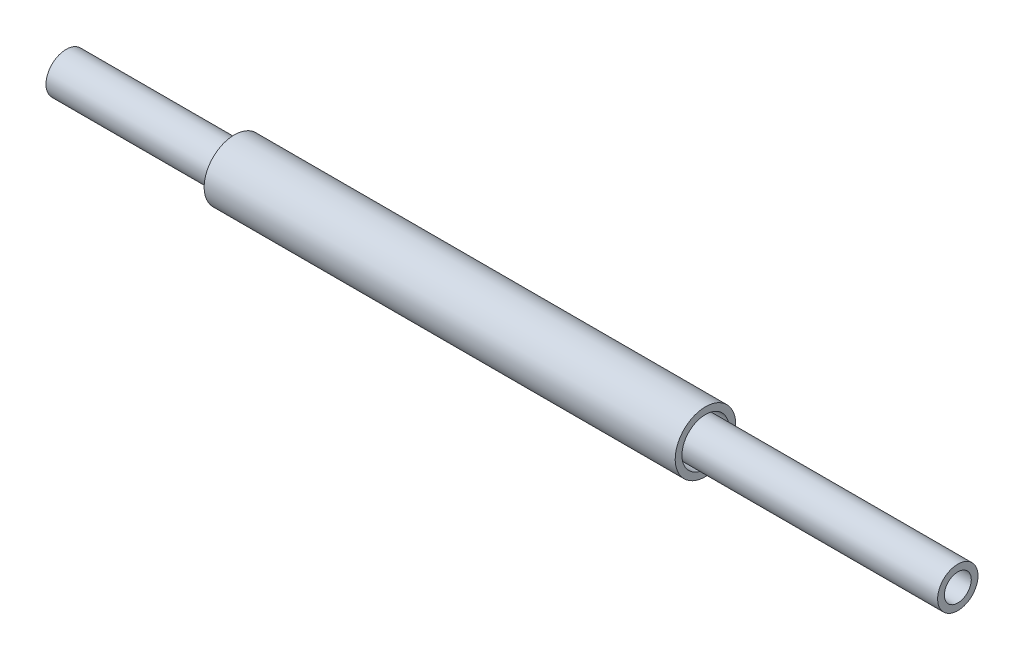
SolidWorks part; units mm, degrees
ref_plane "Front Plane" through (0, 0, 0) normal (0, 0, 1) x (1, 0, 0)
ref_plane "Top Plane" through (0, 0, 0) normal (0, 1, 0) x (1, 0, 0)
ref_plane "Right Plane" through (0, 0, 0) normal (1, 0, 0) x (0, 0, -1)
sketch "Sketch1" plane through (0, 0, 0) normal (0, 0, 1) x (1, 0, 0)
  line L0 (0, 0) -> (8000, 0) construction
  line L1 (900, 80) -> (900, 120)
  line L2 (900, 120) -> (6200, 120)
  line L3 (6200, 120) -> (6200, 80)
  line L4 (6200, 80) -> (900, 80)
revolve "Revolve1" add sketch "Sketch1" angle 360 about L0
sketch "Sketch2" plane through (0, 0, 0) normal (0, 0, 1) x (1, 0, 0)
  line L0 (0, 0) -> (6000, 0) construction
  line L1 (1900, 140) -> (1900, 180)
  line L2 (1900, 180) -> (4700, 180)
  line L3 (4700, 180) -> (4700, 140)
  line L4 (4700, 140) -> (1900, 140)
revolve "Revolve2" add sketch "Sketch2" angle 360 about L0
